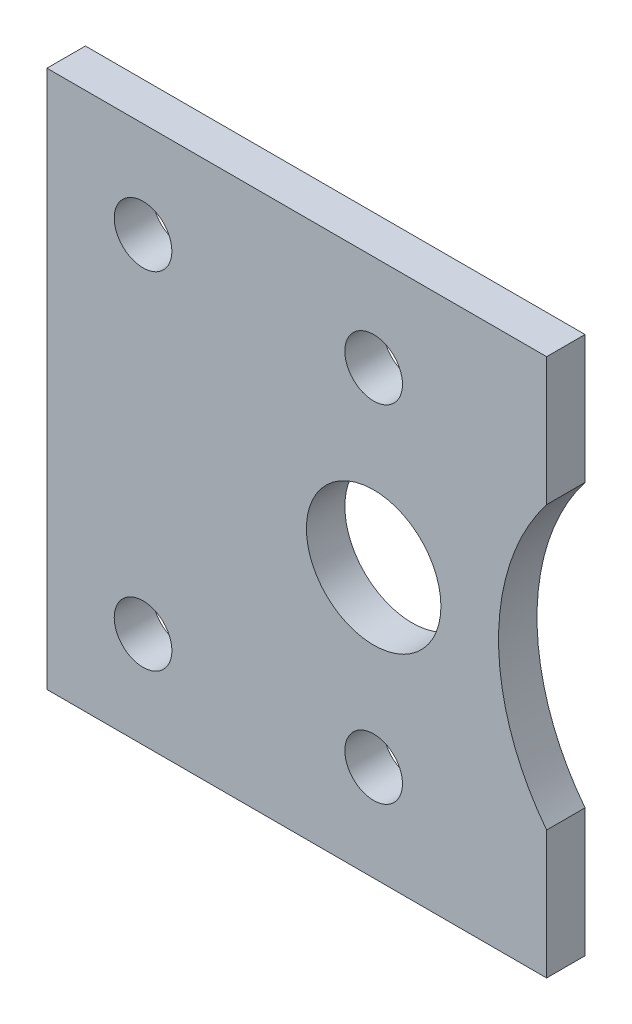
SolidWorks part; units mm, degrees
ref_plane "Front Plane" through (0, 0, 0) normal (0, 0, 1) x (1, 0, 0)
ref_plane "Top Plane" through (0, 0, 0) normal (0, 1, 0) x (1, 0, 0)
ref_plane "Right Plane" through (0, 0, 0) normal (1, 0, 0) x (0, 0, -1)
sketch "Sketch1" plane through (0, 0, 0) normal (0, 0, 1) x (1, 0, 0)
  line L0 (0, 13.0656) -> (0, -15.9465) construction
  line L1 (9, 14) -> (-17, 14)
  line L2 (-17, 14) -> (-17, -14)
  line L3 (-17, -14) -> (9, -14)
  line L4 (9, -14) -> (9, -7.3314)
  line L5 (9, 7.3314) -> (9, 14)
  line L6 (-19.9856, 0) -> (15.932, 0) construction
  circle A0 centre (0, 0) radius 3.5
  circle A2 centre (0, 9) radius 1.5
  arc A3 (9, -7.3314) -> (9, 7.3314) centre (18.5, 0) cw
  circle A4 centre (-12, 9) radius 1.5
  circle A6 centre (-12, -9) radius 1.5
  circle A7 centre (0, -9) radius 1.5
  dimension "D1" = 28
  dimension "D2" = 7
  dimension "D3" = 3
  dimension "D9" = 3
  dimension "D12" = 0
  dimension "D14" = 12
  dimension "D15" = 18.5
  dimension "D5" = 5
  dimension "D6" = 17
  dimension "D7" = 26
  dimension "D10" = 5
  dimension "D13" = 0
extrude "Boss-Extrude1" add sketch "Sketch1" against normal blind 2
